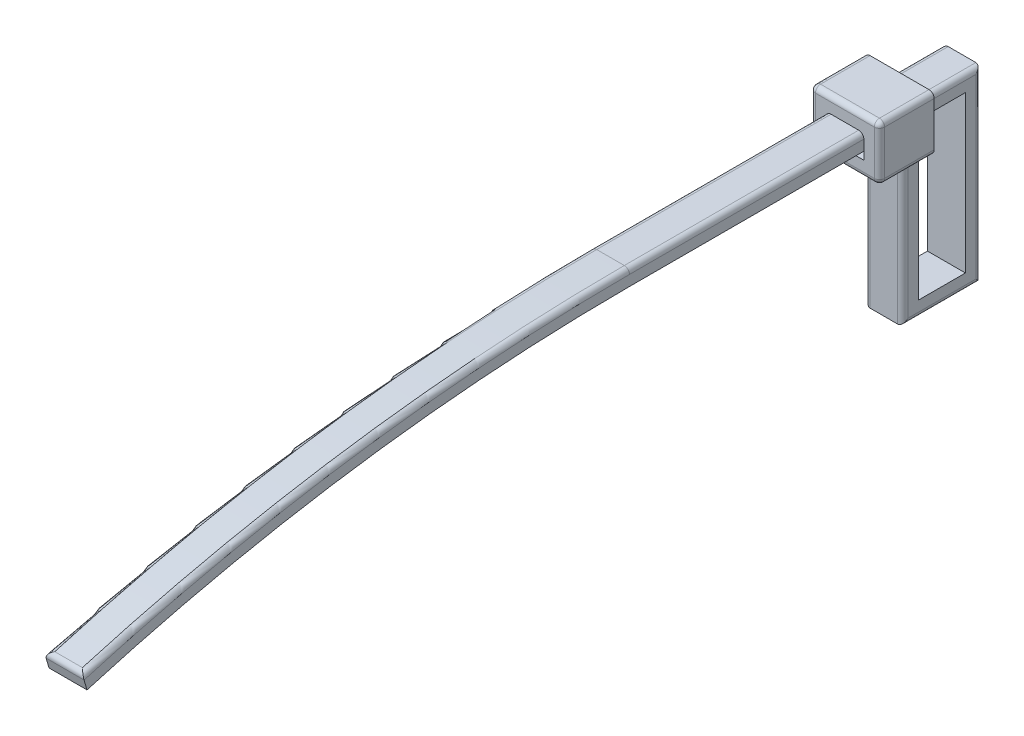
SolidWorks part; units mm, degrees
ref_plane "Plan de face" through (0, 0, 0) normal (0, 0, 1) x (1, 0, 0)
ref_plane "Plan de dessus" through (0, 0, 0) normal (0, 1, 0) x (1, 0, 0)
ref_plane "Plan de droite" through (0, 0, 0) normal (1, 0, 0) x (0, 0, -1)
sketch "Esquisse1" plane through (0, 0, 0) normal (1, 0, 0) x (0, 0, -1)
  line L0 (-20.1045, 0) -> (25.3881, 0) construction
  line L1 (0, 0) -> (5, 0)
  line L2 (5, 0) -> (5, 12)
  line L3 (5, 12) -> (-17.5, 12) construction
  line L4 (-17.5, 12) -> (-17.5, 11)
  line L5 (-17.5, 11) -> (4, 11) construction
  line L6 (4, 11) -> (4, 1)
  line L7 (4, 1) -> (1, 1)
  line L8 (1, 1) -> (1, 11) construction
  line L9 (0, 0) -> (0, 11) construction
  line L10 (-2.5, 12) -> (-2.5, 13) construction
  line L14 (-2.5, 9.5) -> (-2.5, 12) construction
  line L15 (1, 1) -> (1, 11)
  line L16 (0, 0) -> (0, 9.5)
  line L17 (0, 9.5) -> (-2.5, 9.5)
  line L18 (-2.5, 9.5) -> (-2.5, 11)
  line L19 (-2.5, 11) -> (-17.5, 11)
  line L20 (-17.5, 12) -> (-2.5, 12)
  line L21 (-2.5, 12) -> (-2.5, 13)
  line L28 (1, 11) -> (4, 11)
  line L29 (5, 12) -> (1, 12)
  line L30 (1, 12) -> (1, 13)
  line L31 (1, 13) -> (-2.5, 13)
  line L32 (-52.5, 6.9594) -> (-52.2178, 6)
  arc A0 (-17.5, 12) -> (-52.5, 6.9594) centre (-17.5, -112.0327) ccw
  arc A1 (-52.2178, 6) -> (-17.5, 11) centre (-17.5, -112.0327) cw
  point P26 (-90.5107, 29.5716)
  dimension "D10" = 1
  dimension "D1" = 3
  dimension "D2" = 10
  dimension "D3" = 3.5
  dimension "D4" = 1
  dimension "D5" = 1.5
  dimension "D6" = 1
  dimension "D7" = 1
  dimension "D8" = 1
  dimension "D9" = 1
  dimension "D11" = 50
  dimension "D12" = 5
  dimension "D13" = 15
extrude "Boss.-Extru.1" add sketch "Esquisse1" along normal blind 2.43 contours L30 L31 L21 L20 L4 L19 L18 L17 L16 L1 L2 L29 L15 L28 L6 L7 | L32 A1 L4 A0
sketch "Esquisse2" plane through (2.43, 0, 0) normal (1, 0, 0) x (0, 0, -1)
  line L1 (-2.5, 12) -> (-2.5, 11)
  line L3 (0, 9.5) -> (1, 9.5)
  line L4 (1, 1) -> (1, 11) construction
  line L5 (1, 9.5) -> (1, 12)
  line L22 (1, 12) -> (1, 13)
  line L36 (1, 13) -> (-2.5, 13)
  line L37 (-2.5, 13) -> (-2.5, 12)
  line L38 (-2.5, 12) -> (-17.5, 12)
  line L39 (-52.5, 6.9594) -> (-52.2178, 6)
  line L40 (-17.5, 11) -> (-2.5, 11)
  line L41 (-2.5, 11) -> (-2.5, 9.5)
  line L42 (-2.5, 9.5) -> (0, 9.5)
  line L43 (0, 9.5) -> (0, 0)
  line L44 (0, 0) -> (5, 0)
  line L45 (5, 0) -> (5, 12)
  line L46 (5, 12) -> (1, 12)
  line L47 (1, 12) -> (1, 13)
  line L48 (1, 13) -> (-2.5, 13)
  line L49 (-2.5, 13) -> (-2.5, 12)
  line L50 (-2.5, 12) -> (-17.5, 12)
  line L51 (-52.5, 6.9594) -> (-52.2178, 6)
  line L52 (-17.5, 11) -> (-2.5, 11)
  line L53 (-2.5, 11) -> (-2.5, 9.5)
  line L54 (-2.5, 9.5) -> (0, 9.5)
  line L55 (0, 9.5) -> (0, 0)
  line L56 (0, 0) -> (5, 0)
  line L57 (5, 0) -> (5, 12)
  line L58 (5, 12) -> (1, 12)
  arc A2 (-17.5, 12) -> (-52.5, 6.9594) centre (-17.5, -112.0327) ccw
  arc A3 (-17.5, 11) -> (-52.2178, 6) centre (-17.5, -112.0327) ccw
  arc A4 (-17.5, 12) -> (-52.5, 6.9594) centre (-17.5, -112.0327) ccw
  arc A5 (-17.5, 11) -> (-52.2178, 6) centre (-17.5, -112.0327) ccw
  dimension "D1" = 0
extrude "Boss.-Extru.2" add sketch "Esquisse2" along normal blind 1
sketch "Esquisse3" plane through (0, 0, 0) normal (-1, 0, 0) x (0, 0, 1)
  line L4 (-1, 12) -> (-1, 9.5)
  line L5 (-1, 1) -> (-1, 11) construction
  line L6 (-1, 9.5) -> (0, 9.5)
  line L7 (2.5, 11) -> (2.5, 12)
  line L37 (-1, 13) -> (-1, 12)
  line L38 (-1, 12) -> (-5, 12)
  line L39 (-5, 12) -> (-5, 0)
  line L40 (-5, 0) -> (0, 0)
  line L41 (0, 0) -> (0, 9.5)
  line L42 (0, 9.5) -> (2.5, 9.5)
  line L43 (2.5, 9.5) -> (2.5, 11)
  line L44 (2.5, 11) -> (17.5, 11)
  line L45 (52.2178, 6) -> (52.5, 6.9594)
  line L46 (17.5, 12) -> (2.5, 12)
  line L47 (2.5, 12) -> (2.5, 13)
  line L48 (2.5, 13) -> (-1, 13)
  line L49 (-1, 13) -> (-1, 12)
  line L50 (-1, 12) -> (-5, 12)
  line L51 (-5, 12) -> (-5, 0)
  line L52 (-5, 0) -> (0, 0)
  line L53 (0, 0) -> (0, 9.5)
  line L54 (0, 9.5) -> (2.5, 9.5)
  line L55 (2.5, 9.5) -> (2.5, 11)
  line L56 (2.5, 11) -> (17.5, 11)
  line L57 (52.2178, 6) -> (52.5, 6.9594)
  line L58 (17.5, 12) -> (2.5, 12)
  line L59 (2.5, 12) -> (2.5, 13)
  line L60 (2.5, 13) -> (-1, 13)
  arc A2 (52.2178, 6) -> (17.5, 11) centre (17.5, -112.0327) ccw
  arc A3 (52.5, 6.9594) -> (17.5, 12) centre (17.5, -112.0327) ccw
  arc A4 (52.2178, 6) -> (17.5, 11) centre (17.5, -112.0327) ccw
  arc A5 (52.5, 6.9594) -> (17.5, 12) centre (17.5, -112.0327) ccw
  dimension "D1" = 0
extrude "Boss.-Extru.3" add sketch "Esquisse3" along normal blind 1
fillet "Congé1" radius 0.33 21 edges at (1.215, 13, 2.5) (1.215, 9.5, 2.5) (0, 10.7334, 35.1806) (2.43, 10.7334, 35.1806) (1.215, 6.9594, 52.5) (0, 12, 10) (2.43, 12, 10) (3.43, 11.25, 2.5) (-1, 11.25, 2.5) (-1, 13, 0.75) (-1, 9.5, 0.75) (3.43, 9.5, 0.75) (3.43, 13, 0.75) (0, 0, -2.5) (0, 4.75, 0) (2.43, 0, -2.5) (2.43, 4.75, 0) (0, 6, -5) (2.43, 6, -5) (0, 12, -3) (2.43, 12, -3)
sketch "Esquisse4" plane through (0, 0, 2.5) normal (0, 0, 1) x (1, 0, 0)
  line L0 (2.43, 11) -> (0, 11) construction
  line L1 (2.43, 11) -> (0, 11)
  line L2 (0, 11) -> (0, 10.5)
  line L3 (0, 10.5) -> (2.43, 10.5)
  line L4 (-0.67, 9.83) -> (3.1, 9.83)
  line L5 (3.1, 9.83) -> (3.1, 12.67)
  line L6 (3.1, 12.67) -> (-0.67, 12.67)
  line L8 (-0.67, 9.83) -> (3.1, 9.83)
  line L10 (3.1, 12.67) -> (-0.67, 12.67)
  line L12 (2.43, 10.5) -> (2.43, 11)
  line L17 (3.1, 9.83) -> (3.1, 12.67)
  line L19 (-0.67, 12.67) -> (-0.67, 9.83)
  line L20 (-0.67, 12.67) -> (-0.67, 9.83)
  point P7 (2.43, 11.0828)
  line M13 (2.43, 11) -> (0, 11)
  dimension "D2" = 0.5
  dimension "D1" = 0
extrude "Enlèv. mat.-Extru.1" cut sketch "Esquisse4" along direction (0, 0, 1) on the side against the normal blind 2 contours L3 L12 L2 M13
